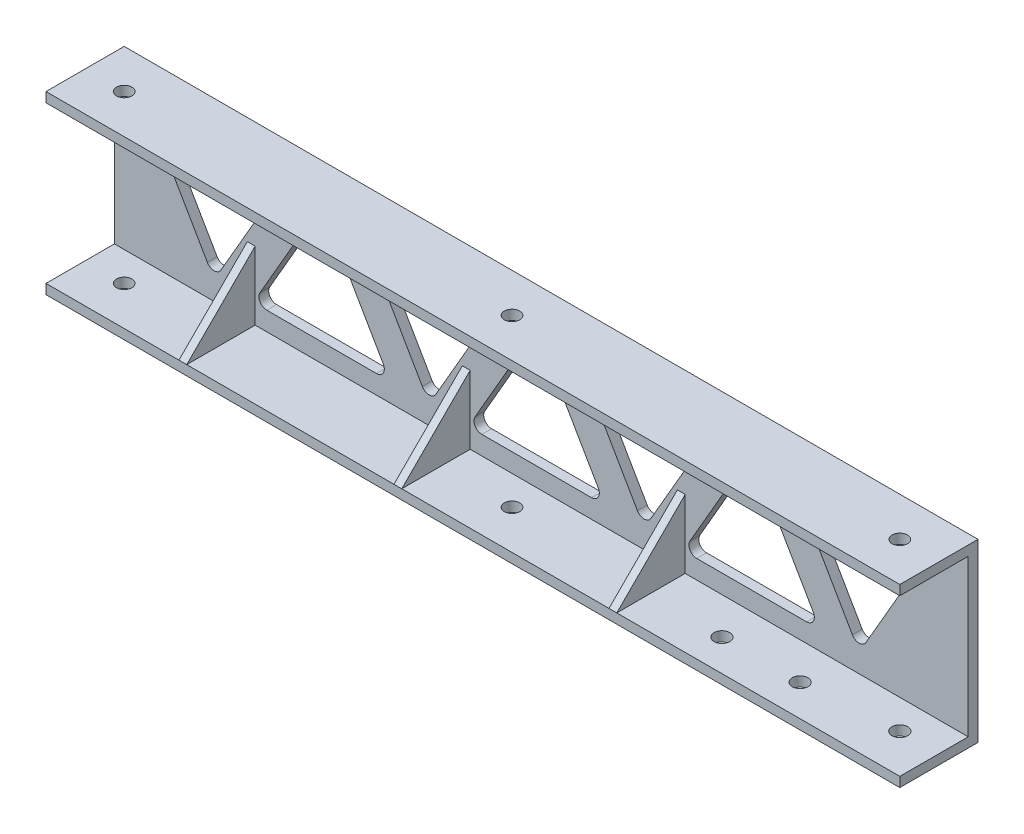
SolidWorks part; units mm, degrees
material "ABS PC"
ref_plane "Front Plane" through (0, 0, 0) normal (0, 0, 1) x (1, 0, 0)
ref_plane "Top Plane" through (0, 0, 0) normal (0, 1, 0) x (1, 0, 0)
ref_plane "Right Plane" through (0, 0, 0) normal (1, 0, 0) x (0, 0, -1)
sketch "Sketch1" plane through (0, 0, 0) normal (0, 0, 1) x (1, 0, 0)
  line L1 (277.368, 0) -> (277.368, 57.15)
  line L2 (277.368, 57.15) -> (0, 57.15)
  line L3 (0, 57.15) -> (0, 0)
  line L4 (0, 0) -> (277.368, 0)
  line L5 (30.1853, 13.081) -> (12.3597, 43.9558)
  line L6 (14.5594, 47.7658) -> (50.2106, 47.7658)
  line L7 (52.4103, 43.9558) -> (34.5847, 13.081)
  line L8 (32.385, 9.271) -> (45.085, 9.271) construction
  line L9 (49.4844, 9.271) -> (85.1356, 9.271)
  line L10 (87.3353, 13.081) -> (69.5097, 43.9558)
  line L11 (65.1103, 43.9558) -> (47.2847, 13.081)
  line L12 (100.0353, 13.081) -> (82.2097, 43.9558)
  line L13 (84.4094, 47.7658) -> (120.0606, 47.7658)
  line L14 (122.2603, 43.9558) -> (104.4347, 13.081)
  line L15 (102.235, 9.271) -> (114.935, 9.271) construction
  line L16 (119.3344, 9.271) -> (154.9856, 9.271)
  line L17 (157.1853, 13.081) -> (139.3597, 43.9558)
  line L18 (134.9603, 43.9558) -> (117.1347, 13.081)
  line L19 (169.8853, 13.081) -> (152.0597, 43.9558)
  line L20 (154.2594, 47.7658) -> (189.9106, 47.7658)
  line L21 (192.1103, 43.9558) -> (174.2847, 13.081)
  line L22 (172.085, 9.271) -> (184.785, 9.271) construction
  line L23 (189.1844, 9.271) -> (224.8356, 9.271)
  line L24 (227.0353, 13.081) -> (209.2097, 43.9558)
  line L25 (204.8103, 43.9558) -> (186.9847, 13.081)
  line L26 (239.7353, 13.081) -> (221.9097, 43.9558)
  line L27 (224.1094, 47.7658) -> (259.7606, 47.7658)
  line L28 (261.9603, 43.9558) -> (244.1347, 13.081)
  line L29 (241.935, 9.271) -> (252.095, 9.271) construction
  arc A0 (259.7606, 47.7658) -> (261.9603, 43.9558) centre (259.7606, 45.2258) cw
  arc A1 (221.9097, 43.9558) -> (224.1094, 47.7658) centre (224.1094, 45.2258) cw
  arc A2 (239.7353, 13.081) -> (244.1347, 13.081) centre (241.935, 14.351) ccw
  arc A3 (189.1844, 9.271) -> (186.9847, 13.081) centre (189.1844, 11.811) cw
  arc A4 (224.8356, 9.271) -> (227.0353, 13.081) centre (224.8356, 11.811) ccw
  arc A5 (209.2097, 43.9558) -> (204.8103, 43.9558) centre (207.01, 42.6858) ccw
  arc A6 (189.9106, 47.7658) -> (192.1103, 43.9558) centre (189.9106, 45.2258) cw
  arc A7 (152.0597, 43.9558) -> (154.2594, 47.7658) centre (154.2594, 45.2258) cw
  arc A8 (169.8853, 13.081) -> (174.2847, 13.081) centre (172.085, 14.351) ccw
  arc A9 (154.9856, 9.271) -> (157.1853, 13.081) centre (154.9856, 11.811) ccw
  arc A10 (119.3344, 9.271) -> (117.1347, 13.081) centre (119.3344, 11.811) cw
  arc A11 (139.3597, 43.9558) -> (134.9603, 43.9558) centre (137.16, 42.6858) ccw
  arc A12 (120.0606, 47.7658) -> (122.2603, 43.9558) centre (120.0606, 45.2258) cw
  arc A13 (82.2097, 43.9558) -> (84.4094, 47.7658) centre (84.4094, 45.2258) cw
  arc A14 (100.0353, 13.081) -> (104.4347, 13.081) centre (102.235, 14.351) ccw
  arc A15 (47.2847, 13.081) -> (49.4844, 9.271) centre (49.4844, 11.811) ccw
  arc A16 (69.5097, 43.9558) -> (65.1103, 43.9558) centre (67.31, 42.6858) ccw
  arc A17 (85.1356, 9.271) -> (87.3353, 13.081) centre (85.1356, 11.811) ccw
  arc A18 (34.5847, 13.081) -> (30.1853, 13.081) centre (32.385, 14.351) cw
  arc A19 (50.2106, 47.7658) -> (52.4103, 43.9558) centre (50.2106, 45.2258) cw
  arc A20 (12.3597, 43.9558) -> (14.5594, 47.7658) centre (14.5594, 45.2258) cw
  point P30 (264.16, 47.7658)
  point P33 (219.71, 47.7658)
  point P42 (229.235, 9.271)
  point P45 (207.01, 47.7658)
  point P48 (194.31, 47.7658)
  point P51 (149.86, 47.7658)
  point P57 (159.385, 9.271)
  point P63 (137.16, 47.7658)
  point P66 (124.46, 47.7658)
  point P69 (80.01, 47.7658)
  point P78 (67.31, 47.7658)
  point P81 (89.535, 9.271)
  point P87 (54.61, 47.7658)
  point P90 (10.16, 47.7658)
  dimension "D35" = 2.54
  dimension "D1" = 44.45
  dimension "D2" = 44.45
  dimension "D3" = 44.45
  dimension "D4" = 10.16
  dimension "D5" = 9.271
  dimension "D6" = 57.15
  dimension "D7" = 44.45
  dimension "D8" = 44.45
  dimension "D9" = 44.45
  dimension "D10" = 12.7
  dimension "D11" = 277.368
  dimension "D12" = 44.45
  dimension "D13" = 44.45
  dimension "D14" = 44.45
  dimension "D15" = 44.45
  dimension "D16" = 44.45
  dimension "D17" = 12.7
  dimension "D18" = 44.45
  dimension "D19" = 44.45
  dimension "D20" = 44.45
  dimension "D21" = 44.45
  dimension "D22" = 44.45
  dimension "D23" = 12.7
  dimension "D24" = 9.271
  dimension "D25" = 12.7
  dimension "D26" = 9.271
  dimension "D27" = 12.7
  dimension "D28" = 44.45
  dimension "D29" = 44.45
  dimension "D30" = 10.16
  dimension "D31" = 9.271
  dimension "D32" = 12.7
  dimension "D33" = 44.45
  dimension "D34" = 44.45
  dimension "D36" = 44.45
extrude "Boss-Extrude1" add sketch "Sketch1" along normal blind 3.175
sketch "Sketch2" plane through (0, 57.15, 0) normal (0, 1, 0) x (1, 0, 0)
  line L0 (0, 0) -> (0, -25.4)
  line L1 (0, -25.4) -> (277.368, -25.4)
  line L2 (277.368, -25.4) -> (277.368, 0)
  line L3 (277.368, 0) -> (0, 0)
  dimension "D1" = 25.4
extrude "Boss-Extrude2" add sketch "Sketch2" against normal blind 3.175
sketch "Sketch3" plane through (0, 0, 0) normal (0, -1, 0) x (1, 0, 0)
  line L0 (0, 0) -> (0, 25.4)
  line L1 (0, 25.4) -> (277.368, 25.4)
  line L2 (277.368, 25.4) -> (277.368, 0)
  line L3 (277.368, 0) -> (0, 0)
extrude "Boss-Extrude3" add sketch "Sketch3" against normal blind 3.175
sketch "Sketch4" plane through (0, 0, 3.175) normal (0, 0, 1) x (1, 0, 0)
  line L0 (0, 3.175) -> (277.368, 3.175) construction
  line L1 (0, 3.175) -> (43.18, 3.175) construction
  line L2 (43.18, 3.175) -> (113.03, 3.175) construction
  line L3 (113.03, 3.175) -> (182.88, 3.175) construction
  line L4 (277.368, 53.975) -> (0, 53.975) construction
  line L5 (0, 53.975) -> (76.708, 53.975) construction
  line L6 (76.708, 53.975) -> (146.558, 53.975) construction
  line L7 (146.558, 53.975) -> (216.408, 53.975) construction
  line L8 (43.18, 3.175) -> (43.18, 20.447) construction
  line L9 (113.03, 3.175) -> (113.03, 20.447) construction
  line L10 (182.88, 3.175) -> (182.88, 20.447) construction
  line L11 (216.408, 53.975) -> (216.408, 36.703) construction
  line L12 (146.558, 53.975) -> (146.558, 36.703) construction
  line L13 (76.708, 53.975) -> (76.708, 36.703) construction
  line L14 (277.368, 3.175) -> (277.368, 53.975) construction
  line L15 (0, 53.975) -> (0, 3.175) construction
  point P24 (113.03, 11.811)
  dimension "D1" = 69.85
  dimension "D2" = 69.85
  dimension "D3" = 60.96
  dimension "D4" = 43.18
  dimension "D5" = 69.85
  dimension "D6" = 69.85
ref_plane "Plane1" through (43.18, 0, 0) normal (1, 0, 0) x (0, 1, 0)
ref_plane "Plane2" through (113.03, 0, 0) normal (1, 0, 0) x (0, 1, 0)
ref_plane "Plane3" through (182.88, 0, 0) normal (1, 0, 0) x (0, 1, 0)
ref_plane "Plane4" through (216.408, 0, 0) normal (-1, 0, 0) x (0, -1, 0)
ref_plane "Plane5" through (146.558, 0, 0) normal (-1, 0, 0) x (0, -1, 0)
ref_plane "Plane6" through (76.708, 0, 0) normal (-1, 0, 0) x (0, -1, 0)
sketch "Sketch5" plane through (43.18, 0, 0) normal (1, 0, 0) x (0, 1, 0)
  line L0 (3.175, 3.175) -> (3.175, 25.4)
  line L1 (3.175, 3.175) -> (25.4, 3.175)
  line L2 (3.175, 3.175) -> (53.975, 3.175) construction
  line L3 (25.4, 3.175) -> (3.175, 25.4)
  dimension "D1" = 22.225
  dimension "D2" = 22.225
extrude "Boss-Extrude4" add sketch "Sketch5" along normal blind 2.54
sketch "Sketch6" plane through (113.03, 0, 0) normal (1, 0, 0) x (0, 1, 0)
  line L0 (3.175, 25.4) -> (3.175, 3.175)
  line L1 (3.175, 3.175) -> (25.4, 3.175)
  line L2 (25.4, 3.175) -> (3.175, 25.4)
extrude "Boss-Extrude5" add sketch "Sketch6" along normal blind 2.54
sketch "Sketch7" plane through (182.88, 0, 0) normal (1, 0, 0) x (0, 1, 0)
  line L0 (3.175, 25.4) -> (3.175, 3.175)
  line L1 (3.175, 3.175) -> (25.4, 3.175)
  line L2 (25.4, 3.175) -> (3.175, 25.4)
extrude "Boss-Extrude6" add sketch "Sketch7" along normal blind 2.54
sketch "Sketch8" plane through (76.708, 0, 0) normal (-1, 0, 0) x (0, -1, 0)
  line L0 (-53.975, 3.175) -> (-53.975, 25.4)
  line L1 (-53.975, 25.4) -> (-31.75, 3.175)
  line L2 (-3.175, 3.175) -> (-53.975, 3.175) construction
  line L3 (-31.75, 3.175) -> (-53.975, 3.175)
extrude "Boss-Extrude7" add sketch "Sketch8" against normal blind 2.54
sketch "Sketch9" plane through (146.558, 0, 0) normal (-1, 0, 0) x (0, -1, 0)
  line L0 (-53.975, 25.4) -> (-53.975, 3.175)
  line L1 (-53.975, 3.175) -> (-31.75, 3.175)
  line L2 (-31.75, 3.175) -> (-53.975, 25.4)
extrude "Boss-Extrude8" add sketch "Sketch9" against normal blind 2.54
sketch "Sketch10" plane through (216.408, 0, 0) normal (-1, 0, 0) x (0, -1, 0)
  line L0 (-53.975, 25.4) -> (-53.975, 3.175)
  line L1 (-53.975, 3.175) -> (-31.75, 3.175)
  line L2 (-31.75, 3.175) -> (-53.975, 25.4)
extrude "Boss-Extrude9" add sketch "Sketch10" against normal blind 2.54
hole_wizard "#10 Clearance Hole1" positions "Sketch11" profile "Sketch12" hole size "#10" standard "ANSI Inch"
sketch "Sketch11" plane through (0, 3.175, 0) normal (0, 1, 0) x (1, 0, 0)
  point P0 (209.2997, -15.125)
  point P3 (234.6997, -15.125)
sketch "Sketch12" plane through (209.2997, 3.175, 15.125) normal (1, 0, 0) x (0, 0, 1)
  line L0 (0, 0) -> (0, 3.175)
  line L1 (0, 3.175) -> (2.5527, 3.175)
  line L2 (2.5527, 3.175) -> (2.5527, 0)
  line L5 (2.5527, 0) -> (0, 0)
  line L11 (0, -6.35) -> (0, 107.95) construction
  dimension "Thru Hole Dia." = 5.1054
  dimension "Thru Hole Depth" = 3.175
hole_wizard "#10 Clearance Hole2" positions "Sketch17" profile "Sketch16" hole size "#10" standard "ANSI Inch"
sketch "Sketch17" plane through (0, 3.175, 0) normal (0, 1, 0) x (1, 0, 0)
  point P0 (264.668, -12.7)
sketch "Sketch16" plane through (264.668, 3.175, 12.7) normal (1, 0, 0) x (0, 0, 1)
  line L0 (0, 0) -> (0, 3.175)
  line L1 (0, 3.175) -> (2.5527, 3.175)
  line L2 (2.5527, 3.175) -> (2.5527, 0)
  line L5 (2.5527, 0) -> (0, 0)
  line L11 (0, -6.35) -> (0, 107.95) construction
  dimension "Thru Hole Dia." = 5.1054
  dimension "Thru Hole Depth" = 3.175
hole_wizard "#10 Clearance Hole3" positions "Sketch18" profile "Sketch19" hole size "#10" standard "ANSI Inch"
sketch "Sketch18" plane through (0, 3.175, 0) normal (0, 1, 0) x (1, 0, 0)
  point P0 (138.684, -12.7)
  point P3 (264.668, -12.7)
  point P6 (12.7, -12.7)
sketch "Sketch19" plane through (138.684, 3.175, 12.7) normal (1, 0, 0) x (0, 0, 1)
  line L0 (0, 0) -> (0, 3.175)
  line L1 (0, 3.175) -> (2.4892, 3.175)
  line L2 (2.4892, 3.175) -> (2.4892, 0)
  line L5 (2.4892, 0) -> (0, 0)
  line L11 (0, -6.35) -> (0, 107.95) construction
  dimension "Thru Hole Dia." = 4.9784
  dimension "Thru Hole Depth" = 3.175
hole_wizard "#10 Clearance Hole4" positions "Sketch20" profile "Sketch21" hole size "#10" standard "ANSI Inch" end condition through all
sketch "Sketch20" plane through (0, 53.975, 0) normal (0, -1, 0) x (-1, 0, 0)
  point P0 (-138.684, -12.7)
  point P3 (-264.668, -12.7)
  point P6 (-12.7, -12.7)
sketch "Sketch21" plane through (138.684, 53.975, 12.7) normal (1, 0, 0) x (0, 0, -1)
  line L0 (0, 0) -> (0, 3.175)
  line L1 (0, 3.175) -> (2.4892, 3.175)
  line L2 (2.4892, 3.175) -> (2.4892, 0)
  line L5 (2.4892, 0) -> (0, 0)
  line L11 (0, -6.35) -> (0, 107.95) construction
  dimension "Thru Hole Dia." = 4.9784
  dimension "Thru Hole Depth" = 3.175
sketch "Sketch22" plane through (0, 53.975, 0) normal (0, -1, 0) x (1, 0, 0)
  circle A0 centre (234.6997, 15.125) radius 3.7703
  circle A1 centre (209.2997, 15.125) radius 4.0621
extrude "Boss-Extrude10" add sketch "Sketch22" against normal blind 3.175
